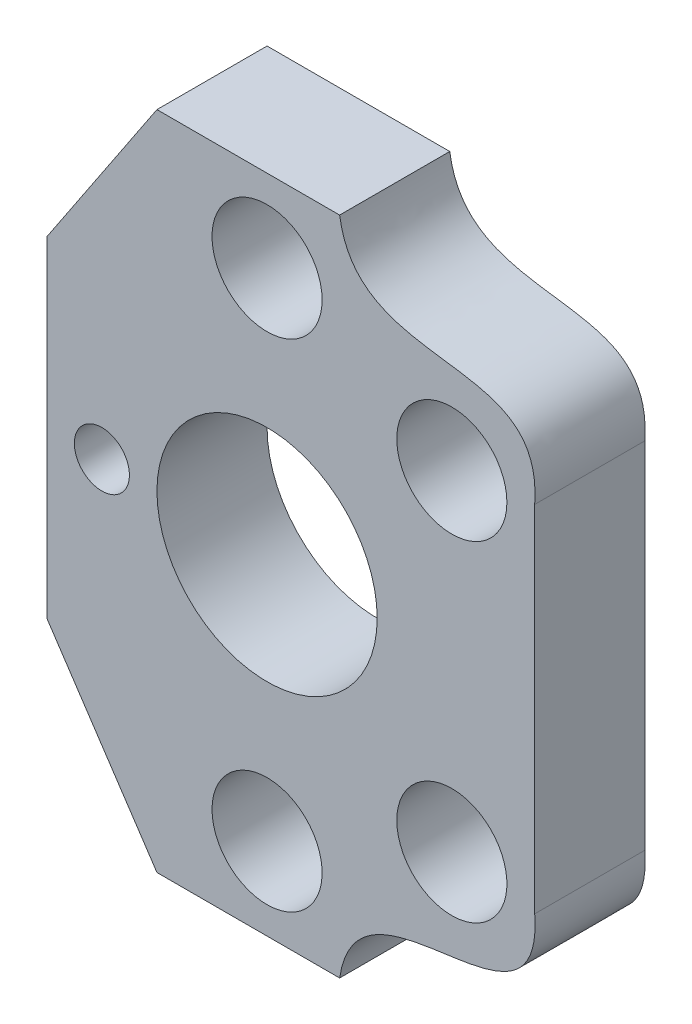
SolidWorks part; units mm, degrees
ref_plane "Front Plane" through (0, 0, 0) normal (0, 0, 1) x (1, 0, 0)
ref_plane "Top Plane" through (0, 0, 0) normal (0, 1, 0) x (1, 0, 0)
ref_plane "Right Plane" through (0, 0, 0) normal (1, 0, 0) x (0, 0, -1)
sketch "Sketch1" plane through (0, 0, 0) normal (0, 0, 1) x (1, 0, 0)
  line L0 (0, -1014.8131) -> (0, -34.9367) construction
  line L1 (-1016.0396, -7.4066) -> (-17.5, -7.4066) construction
  line L2 (-20, -22.4066) -> (-20, 7.5934)
  line L3 (-20, 7.5934) -> (-10, 22.5934)
  line L4 (-10, 22.5934) -> (0, 22.5934)
  line L5 (0, 22.5934) -> (6.5897, 22.5934)
  line L6 (24.3041, 8.6921) -> (24.3041, -23.5052)
  line L7 (0, -37.4066) -> (6.5897, -37.4066)
  line L8 (-10, -37.4066) -> (0, -37.4066)
  line L9 (-20, -22.4066) -> (-10, -37.4066)
  line L10 (0, 1020) -> (0, 20.1236) construction
  line L11 (0, 2.5934) -> (0, 10.1236) construction
  line L12 (0, -17.4066) -> (0, -24.9367) construction
  line L13 (10, -7.4066) -> (22.0792, -7.4066) construction
  line L14 (0, 10.1236) -> (0, 2.5934) construction
  line L15 (0, 20.1236) -> (0, 1024.6727) construction
  line L16 (-12.5, -7.4066) -> (-10, -7.4066) construction
  line L17 (0, -24.9367) -> (0, -17.4066) construction
  line L18 (0, -34.9367) -> (0, -1039.4858) construction
  circle A0 centre (0, -7.4066) radius 10
  circle A1 centre (-15, -7.4066) radius 2.5
  circle A2 centre (0, 15.1236) radius 5
  circle A3 centre (16.7794, 7.5934) radius 5
  circle A4 centre (0, -29.9367) radius 5
  circle A5 centre (16.7794, -22.4066) radius 5
  spline S0 degree 3 poles (6.5897, 22.5934) (8.2798, 11.4356) (25.1655, 20.4776) (24.3041, 8.6921) knots 0 0 0 0 1 1 1 1
  spline S1 degree 3 poles (6.5897, -37.4066) (8.2798, -26.2487) (25.1655, -35.2908) (24.3041, -23.5052) knots 0 0 0 0 1 1 1 1
  point P7 (24.3041, -7.4066)
  point P13 (-20, -7.4066)
  dimension "D5" = 5
  dimension "D6" = 10
  dimension "D7" = 10
  dimension "D1" = 20
  dimension "D2" = 15
  dimension "D3" = 30
  dimension "D4" = 10
extrude "Boss-Extrude1" add sketch "Sketch1" along normal blind 10
